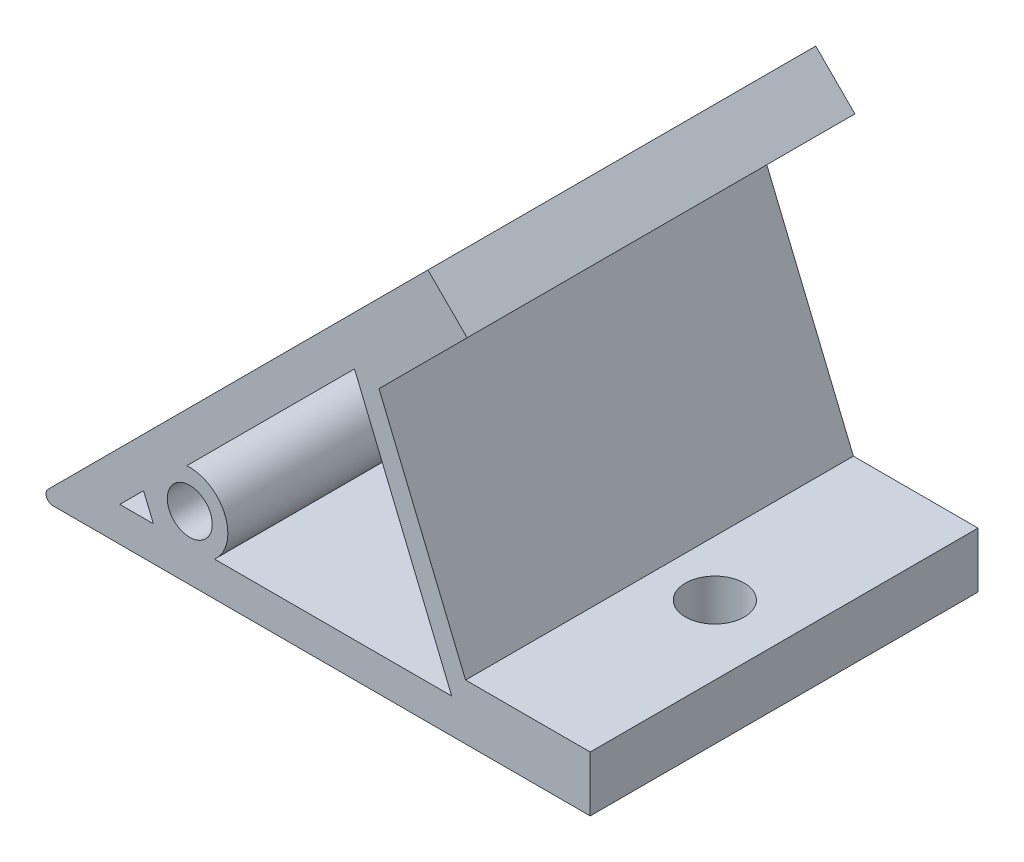
SolidWorks part; units mm, degrees
ref_plane "前视基准面" through (0, 0, 0) normal (0, 0, 1) x (1, 0, 0)
ref_plane "上视基准面" through (0, 0, 0) normal (0, 1, 0) x (1, 0, 0)
ref_plane "右视基准面" through (0, 0, 0) normal (1, 0, 0) x (0, 0, -1)
sketch "草图1" plane through (0, 0, 0) normal (0, 0, 1) x (1, 0, 0)
  line B0 (-77.5858, 0) -> (0, 0)
  line B1 (-67.9289, 5) -> (-63.0745, 5)
  line B2 (-54.2575, 5) -> (-20, 5)
  line B3 (-17.9955, 8) -> (0, 8)
  line B4 (-78.2929, 1.7071) -> (-23.4315, 56.5685)
  line B5 (-67.9289, 5) -> (-64.4963, 8.4326)
  line B6 (-58.2617, 14.6672) -> (-34.0381, 38.8909)
  line B7 (-30.4993, 38.187) -> (-17.7746, 50.9117)
  line B8 (0, 0) -> (0, 8)
  line B9 (-17.7746, 50.9117) -> (-23.4315, 56.5685)
  line B10 (-20, 5) -> (-34.0381, 38.8909)
  line B11 (-17.9955, 8) -> (-30.4993, 38.187)
  line B12 (-63.0745, 5) -> (-64.4963, 8.4326)
  arc B13 (-78.2929, 1.7071) -> (-77.5858, 0) centre (-77.5858, 1) ccw
  circle B14 centre (-57.8269, 9.1844) radius 3.25
  arc B15 (-54.2575, 5) -> (-58.2617, 14.6672) centre (-57.8269, 9.1844) ccw
sketch_block_instance "A$C18907C9D-1"
sketch_block "A$C18907C9D"
extrude "凸台-拉伸1" add sketch "草图1" along normal mid plane 56
sketch "草图3" plane through (0, 8, 0) normal (0, 1, 0) x (1, 0, 0)
  line L0 (0, -28) -> (0, 28) construction
  circle A0 centre (-10, 0) radius 4.25
  dimension "D1" = 10
extrude "切除-拉伸1" cut sketch "草图3" against normal blind 17
sketch "草图4" plane through (-12.5317, -5.1908, 0) normal (0.9239, 0.3827, 0) x (0, 0, -1)
  line L0 (-28, 30.6147) -> (28, 30.6147) construction
  line L1 (-28, 14.2776) -> (-28, 46.9517) construction
  line L2 (28, 14.2776) -> (28, 46.9517) construction
ref_plane "基准面2" through (-11.7157, 28.2843, 0) normal (-0.3827, 0.9239, 0) x (0.9239, 0.3827, 0)
mirror "镜向1" about plane through (-11.7157, 28.2843, 0) normal (-0.3827, 0.9239, 0) of "切除-拉伸1"
